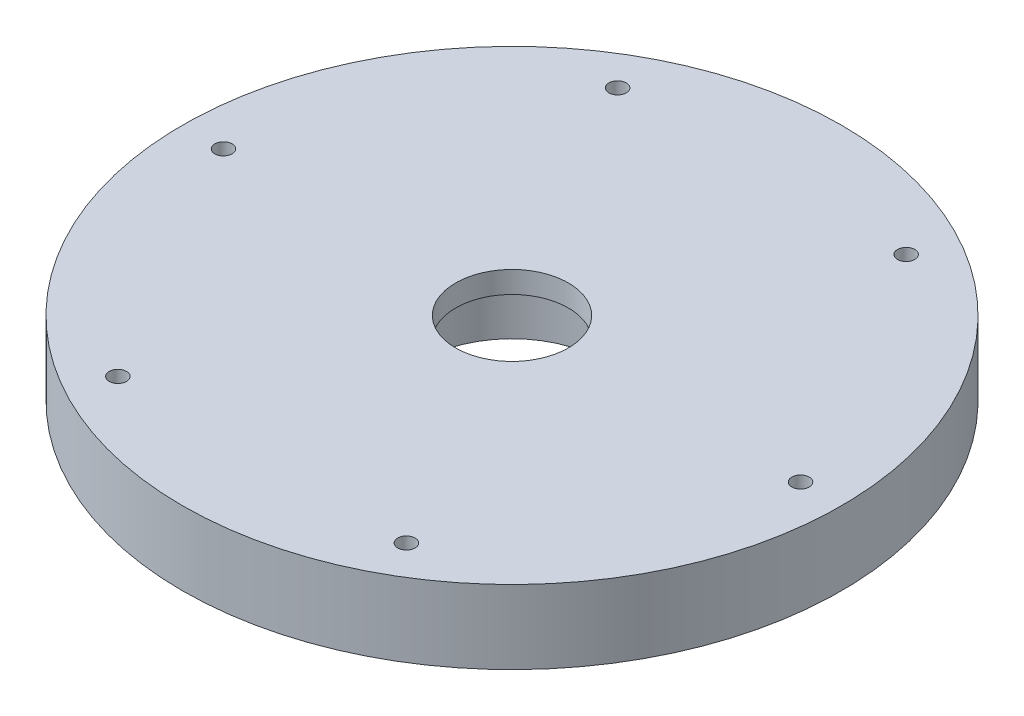
SolidWorks part; units mm, degrees
material "1060 Alloy"
ref_plane "Front Plane" through (0, 0, 0) normal (0, 0, 1) x (1, 0, 0)
ref_plane "Top Plane" through (0, 0, 0) normal (0, 1, 0) x (1, 0, 0)
ref_plane "Right Plane" through (0, 0, 0) normal (1, 0, 0) x (0, 0, -1)
sketch "Sketch1" plane through (0, 0, 0) normal (0, 0, 1) x (1, 0, 0)
  line L0 (0, 38.7087) -> (0, -19.5852) construction
  line L1 (-6.5, 0) -> (-38, 0)
  line L2 (-38, 0) -> (-38, -8.5)
  line L4 (-10.5, -9.75) -> (-10.5, -2.5)
  line L5 (-10.5, -2.5) -> (-6.5, -2.5)
  line L6 (-6.5, -2.5) -> (-6.5, 0)
  line L7 (-10.5, -9.75) -> (-35, -9.75)
  line L8 (-35, -9.75) -> (-35, -8.5)
  line L9 (-35, -8.5) -> (-38, -8.5)
  dimension "D1" = 6.5
  dimension "D2" = 10.5
  dimension "D4" = 38
  dimension "D5" = 3
  dimension "D6" = 1.25
  dimension "D7" = 2.5
  dimension "D3" = 6
revolve "Revolve1" add sketch "Sketch1" angle 360 about L0
sketch "Sketch2" plane through (0, -9.75, 0) normal (0, -1, 0) x (1, 0, 0)
  circle A0 centre (0, 0) radius 33.2687 construction
  circle A1 centre (-33.2687, 0) radius 1
  circle A2 centre (-16.6344, 28.8116) radius 1
  circle A3 centre (16.6344, 28.8116) radius 1
  circle A4 centre (33.2687, 0) radius 1
  circle A5 centre (16.6344, -28.8116) radius 1
  circle A6 centre (-16.6344, -28.8116) radius 1
  point P17 (0, 0)
  dimension "D1" = 2
  dimension "D3" = 66.5375
  dimension "D2" = 6
extrude "Cut-Extrude1" cut sketch "Sketch2" against normal through all
equation "\"Stator_OD\"= 60'No Tolerance given"
equation "\"A\"=35.81 'taken off spec sheet for 06808 (A)"
equation "\"Rotor_ID\"= 30'No Tolerance Given"
equation "\"back_bearing_Thickness\"= 5'-0.12"
equation "\"back_bearing_OD\"= 24'-0.009 https://www.mcmaster.com/5972K155/"
equation "\"Stator_Gap\"= 0.0375'+- 0.0125 (From 1.3.3.1 Kollmorgen manual)"
equation "\"Back_mount_hole\"= 1.75'To be tapped to M2 (USE LOCKTITE)"
equation "\"facePlate_Mount_Hole\"= 2.75'To be tapped to M3"
equation "\"back_bearing_ID\"= 15'"
equation "\"final_shaftD\"= 12'To fit in harmonic"
equation "\"final_shaftL\"= 5.25+3+\"sheet_thick\"+\"connector_thick\"-3+\"harmon_coupleL\"+0.5-\"shaft_Ladjust\"'length to make everything nice and aligned"
equation "\"back_bearing_IDOD\"= 16.5'measured off CAD, actually 16.75, but rounded down to nicer number"
equation "\"rotor_shaftD\"= \"Rotor_ID\" - (\"rotor-shaft_gap\")*2'"
equation "\"front_bearing_ID\"= 12'https://www.mcmaster.com/5972K154/"
equation "\"front_bearing_OD\"= 21'-0.009"
equation "\"front_bearing_IDOD\"= 13.5'Measured off CAD. Actually 13.75, but rounded down"
equation "\"front_bearing_Thickness\"= 5'-0.12"
equation "\"rotor_thickness\"= 2.4'measured off CAD"
equation "\"rotor_height\"= 32.86'+-0.075 taken off spec sheet for 06826 (C)"
equation "\"D1@Sketch1\"=\"final_shaftD\"/2+0.5"
equation "\"D2@Sketch1\"=\"front_bearing_OD\"/2"
equation "\"D4@Sketch1\"=\"Stator_OD\"/2+8"
equation "\"D3@Sketch1\"=\"front_bearing_Thickness\"+1"
equation "\"D3@Sketch2\"=\"Stator_OD\" + \"Stator_Gap\"  + 6.5"
equation "\"D1@Sketch2\"=\"Back_mount_hole\"+0.25"
equation "\"rotor-shaft_gap\"= 0.0185 '+-0.0065 (from manual)"
equation "\"B\"= 26.3'+-0.35 taken off spec sheet for 06826"
equation "\"key_L\"= 20'-0.2 https://www.mcmaster.com/2977N19/"
equation "\"key_H\"= 4'-0.03"
equation "\"key_W\"= 4'-0.03"
equation "\"harmon_keyH\"= 13.8'+0.1 from drawing"
equation "\"harmon_coupleL\"= 21.5' taken from drawing https://www.harmonicdrive.net/_hd/content/caddownloads/dxf/csg-2uh-lw_gearheads/csg-20-100-2uh-lw.pdf"
equation "\"harmon_diam\"= 93' from drawing"
equation "\"harmon_BCD\"= 82' from drawing"
equation "\"harmon_holeD1\"= 5.5' from drawing"
equation "\"harmon_holeD2\"= 5' from drawing"
equation "\"harmon_holeAng\"= 22.5' from drawing"
equation "\"sheet_thick\"= 1/8*25.4 'random, replace w actual sheet thickness when u feel like :)"
equation "\"nut-thickness\"= 5 'idk measure the ones in the shop and adjust"
equation "\"connector_thick\"= 10' random for now"
equation "\"shaft_Ladjust\"= 6.5' sorry. It's silly, but it works."
